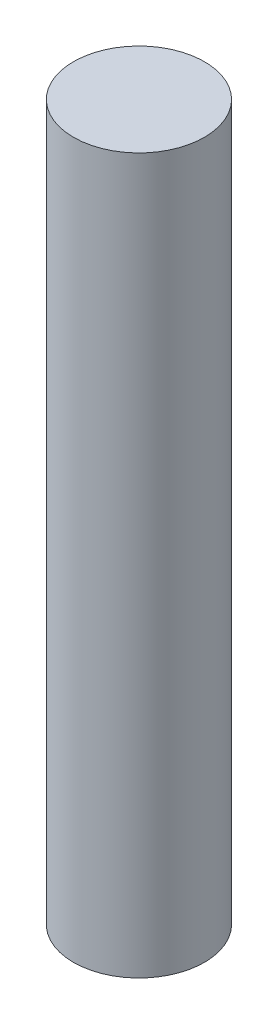
SolidWorks part; units mm, degrees
ref_plane "Front Plane" through (0, 0, 0) normal (0, 0, 1) x (1, 0, 0)
ref_plane "Top Plane" through (0, 0, 0) normal (0, 1, 0) x (1, 0, 0)
ref_plane "Right Plane" through (0, 0, 0) normal (1, 0, 0) x (0, 0, -1)
sketch "Sketch1" plane through (0, 0, 0) normal (0, 1, 0) x (1, 0, 0)
  circle A0 centre (0, 0) radius 5.5
  dimension "D1" = 11
extrude "Boss-Extrude1" add sketch "Sketch1" along normal blind 60
